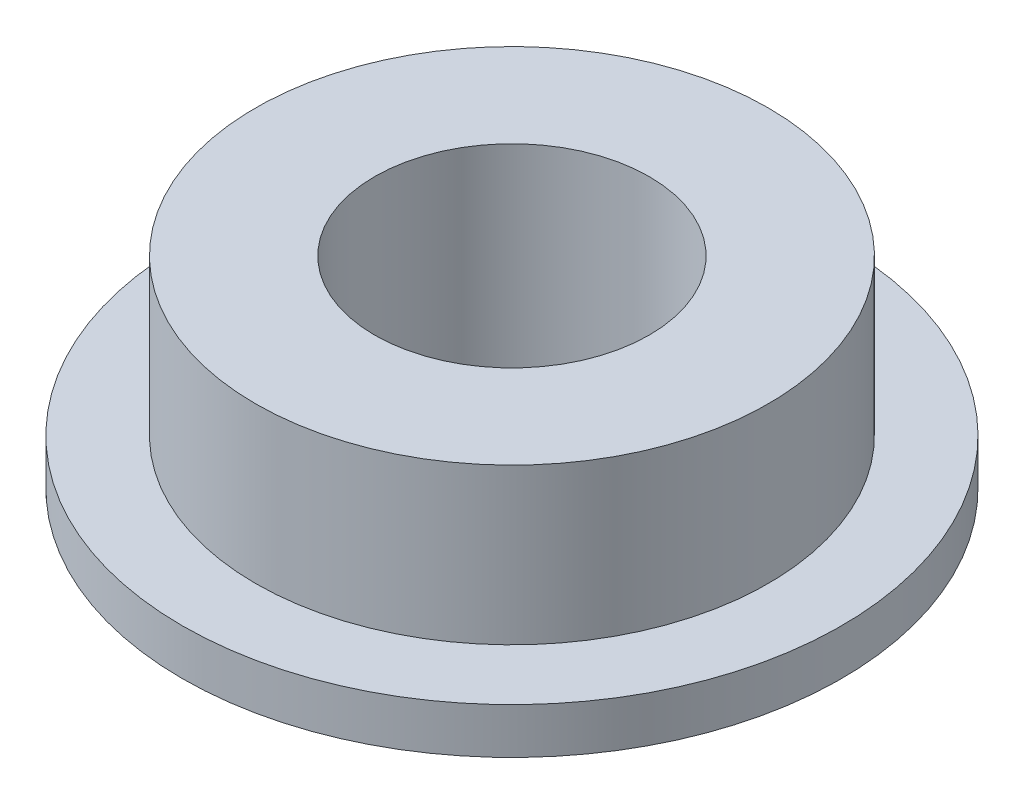
SolidWorks part; units mm, degrees
ref_plane "前基準面" through (0, 0, 0) normal (0, 0, 1) x (1, 0, 0)
ref_plane "上基準面" through (0, 0, 0) normal (0, 1, 0) x (1, 0, 0)
ref_plane "右基準面" through (0, 0, 0) normal (1, 0, 0) x (0, 0, -1)
sketch "草圖1" plane through (0, 0, 0) normal (0, 1, 0) x (1, 0, 0)
  circle A0 centre (0, 0) radius 18
  circle A1 centre (0, 0) radius 7.5
  dimension "D1" = 36
  dimension "D2" = 15
extrude "填料-伸長1" add sketch "草圖1" along normal blind 2.5
sketch "草圖2" plane through (0, 2.5, 0) normal (0, 1, 0) x (1, 0, 0)
  circle A0 centre (0, 0) radius 14
  circle A1 centre (0, 0) radius 7.5
  dimension "D1" = 28
  dimension "D2" = 15
extrude "填料-伸長2" add sketch "草圖2" along normal blind 8.5
